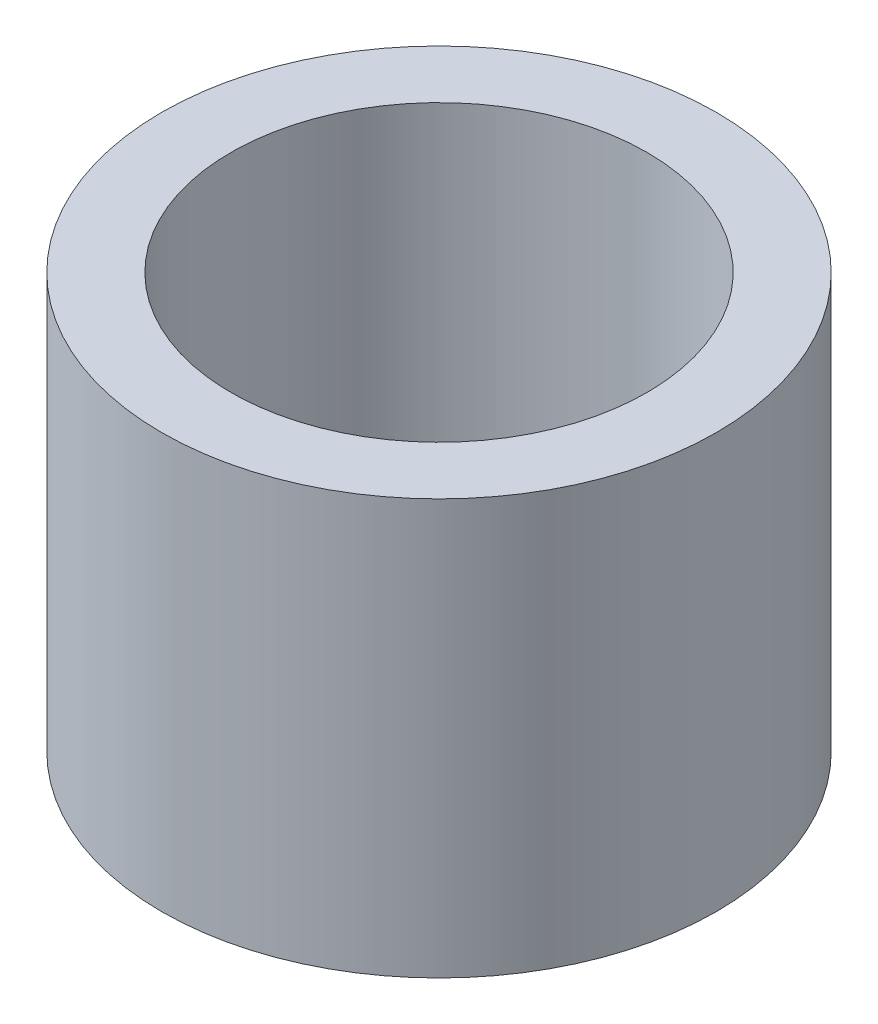
SolidWorks part; units mm, degrees
ref_plane "Front Plane" through (0, 0, 0) normal (0, 0, 1) x (1, 0, 0)
ref_plane "Top Plane" through (0, 0, 0) normal (0, 1, 0) x (1, 0, 0)
ref_plane "Right Plane" through (0, 0, 0) normal (1, 0, 0) x (0, 0, -1)
sketch "Sketch1" plane through (0, 0, 0) normal (0, 1, 0) x (1, 0, 0)
  line L0 (-26.4842, 0) -> (30.2676, 0) construction
  circle A0 centre (0, 0) radius 12.7
  dimension "D1" = 25.4
extrude "Boss-Extrude1" add sketch "Sketch1" along normal blind 19
sketch "Sketch2" plane through (0, 0, 0) normal (0, -1, 0) x (1, 0, 0)
  circle A0 centre (0, 0) radius 9.525
  dimension "D1" = 19.05
extrude "Cut-Extrude1" cut sketch "Sketch2" against normal blind 19
